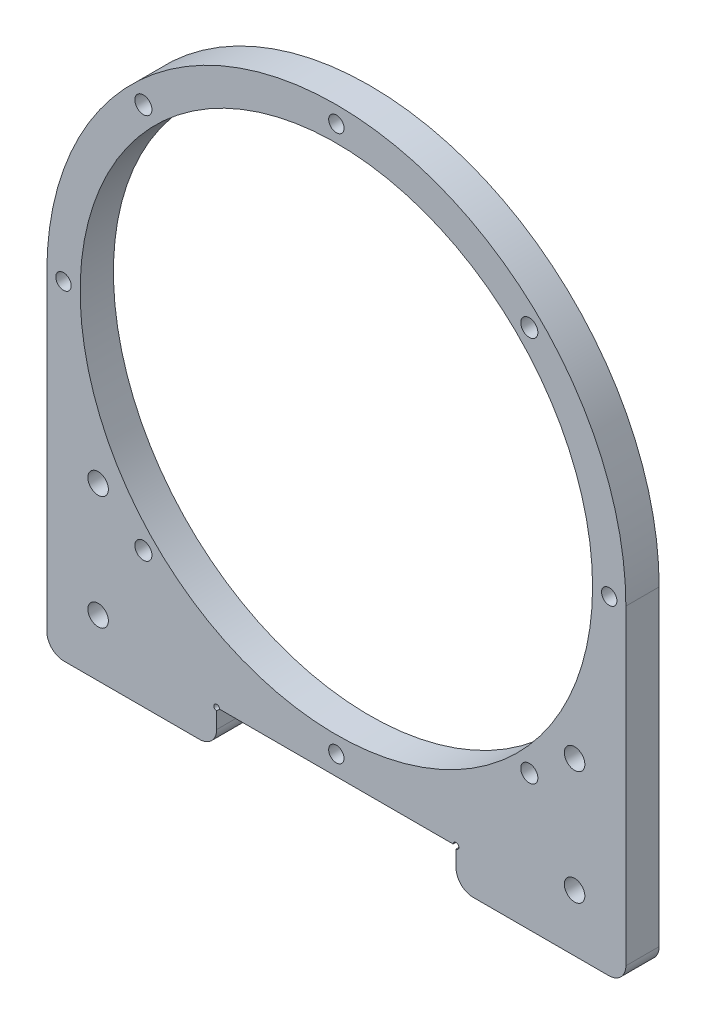
SolidWorks part; units mm, degrees
material "1060 Alloy"
ref_plane "Front Plane" through (0, 0, 0) normal (0, 0, 1) x (1, 0, 0)
ref_plane "Top Plane" through (0, 0, 0) normal (0, 1, 0) x (1, 0, 0)
ref_plane "Right Plane" through (0, 0, 0) normal (1, 0, 0) x (0, 0, -1)
sketch "Sketch1" plane through (0, 0, 0) normal (0, 0, 1) x (1, 0, 0)
  line L0 (-50.8, 0) -> (-50.8, -57.658)
  line L1 (-50.8, 0) -> (-44.958, 0) construction
  line L2 (0, 0) -> (0, -57.658) construction
  line L4 (50.8, 0) -> (50.8, -57.658)
  line L5 (-33.8556, 33.8556) -> (0, 0) construction
  line L8 (0, 0) -> (0, 47.879) construction
  line L12 (-50.8, -57.658) -> (50.8, -57.658)
  line L13 (-41.8, -57.658) -> (-41.8, -47.658) construction
  line L14 (-41.8, -47.658) -> (-41.8, -27.658) construction
  circle A0 centre (41.8, -47.658) radius 1.8
  circle A1 centre (0, 0) radius 44.958
  arc A2 (-50.8, 0) -> (50.8, 0) centre (0, 0) cw
  circle A3 centre (-47.879, 0) radius 1.35
  circle A4 centre (0, 47.879) radius 1.35
  circle A5 centre (41.8, -27.658) radius 1.8
  circle A6 centre (47.879, 0) radius 1.35
  circle A7 centre (0, -47.879) radius 1.35
  circle A10 centre (-41.8, -27.658) radius 1.8
  circle A11 centre (-33.8556, 33.8556) radius 1.5
  circle A12 centre (33.8556, 33.8556) radius 1.5
  circle A13 centre (33.8556, -33.8556) radius 1.5
  circle A14 centre (-33.8556, -33.8556) radius 1.5
  circle A15 centre (-41.8, -47.658) radius 1.8
  point P29 (0, 0)
  point P46 (0, 0)
  dimension "D2" = 89.916
  dimension "D5" = 2.7
  dimension "D6" = 4
  dimension "D7" = 45
  dimension "D14" = 3
  dimension "D17" = 3.6
  dimension "D4" = 101.6
  dimension "D3" = 57.658
  dimension "D18" = 20
  dimension "D19" = 10
  dimension "D20" = 9
  dimension "D15" = 4
extrude "Boss-Extrude1" add sketch "Sketch1" along normal blind 5.842
sketch "Sketch2" plane through (0, 0, 5.842) normal (0, 0, 1) x (1, 0, 0)
  line L0 (0, -57.658) -> (0, -51.308) construction
  line L1 (-50.8, -57.658) -> (50.8, -57.658) construction
  line L3 (-21, -57.658) -> (21, -57.658)
  line L4 (-21, -57.658) -> (-21, -51.308)
  line L5 (-21, -51.308) -> (21, -51.308)
  line L6 (21, -57.658) -> (21, -51.308)
  dimension "D1" = 6.35
  dimension "D2" = 42
extrude "Cut-Extrude1" cut sketch "Sketch2" against normal through all
sketch "Sketch3" plane through (0, 0, 5.842) normal (0, 0, 1) x (1, 0, 0)
  circle A0 centre (-21, -51.308) radius 0.5
  circle A1 centre (21, -51.308) radius 0.5
  dimension "D1" = 1
extrude "Cut-Extrude2" cut sketch "Sketch3" against normal through all
fillet "Fillet1" radius 3 4 edges at (50.8, -57.658, 2.921) (21, -57.658, 2.921) (-21, -57.658, 2.921) (-50.8, -57.658, 2.921)
